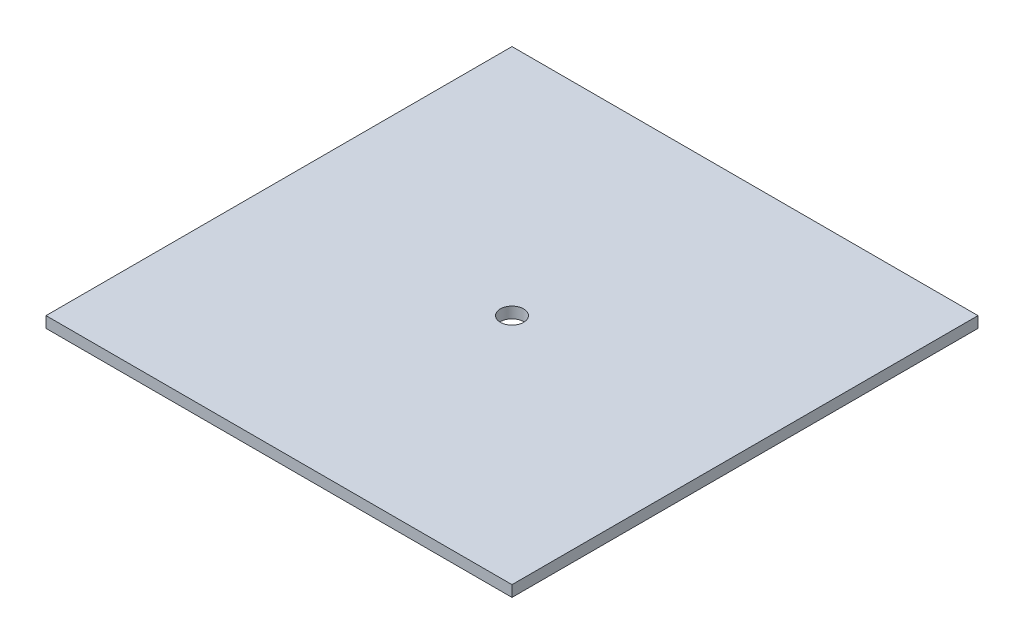
SolidWorks part; units mm, degrees
ref_plane "Front Plane" through (0, 0, 0) normal (0, 0, 1) x (1, 0, 0)
ref_plane "Top Plane" through (0, 0, 0) normal (0, 1, 0) x (1, 0, 0)
ref_plane "Right Plane" through (0, 0, 0) normal (1, 0, 0) x (0, 0, -1)
sketch "Sketch1" plane through (0, 0, 0) normal (0, 1, 0) x (1, 0, 0)
  line L0 (-100, 0) -> (-100, 200) construction
  line L1 (-200, 200) -> (0, 200)
  line L2 (-200, 200) -> (-200, 0)
  line L3 (-200, 0) -> (0, 0)
  line L4 (0, 200) -> (0, 0)
  circle A0 centre (-100, 100) radius 5
  dimension "D3" = 10
  dimension "D1" = 200
  dimension "D2" = 200
extrude "Boss-Extrude1" add sketch "Sketch1" along normal blind 4.7625
